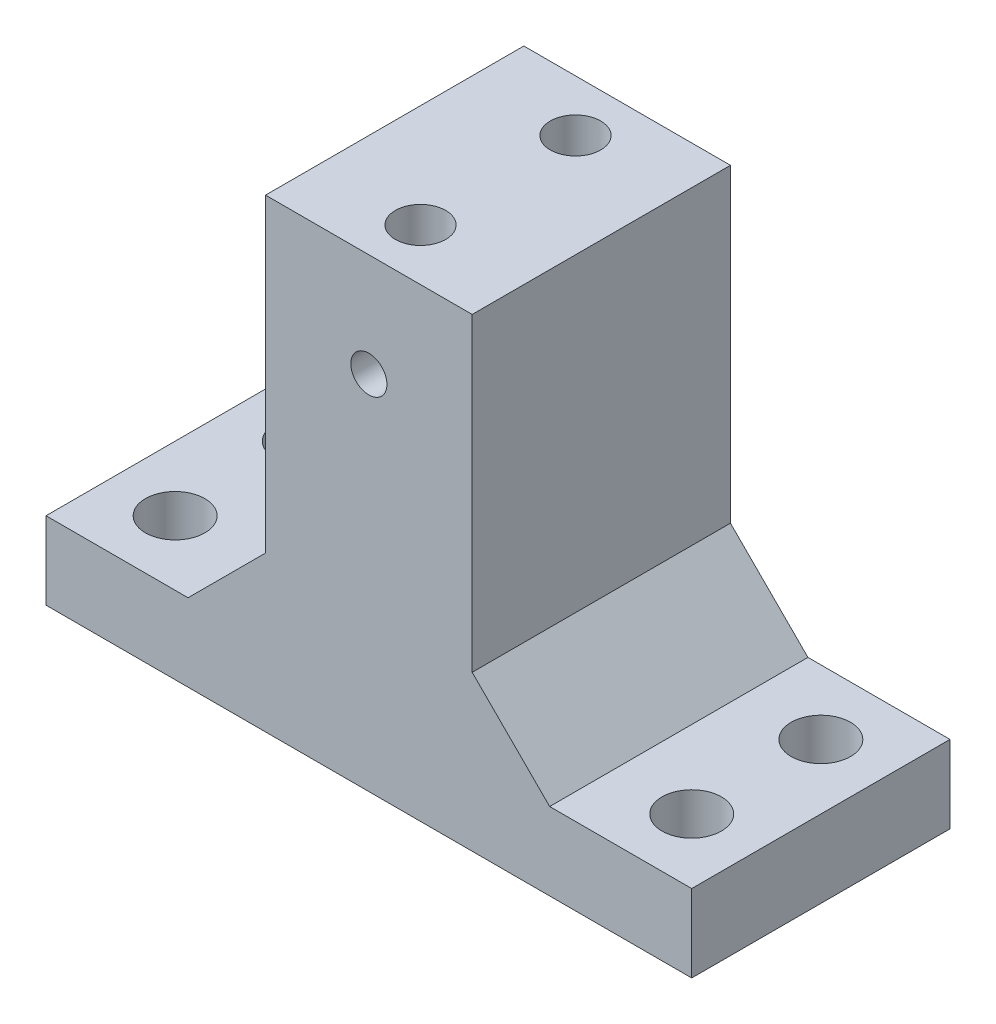
SolidWorks part; units mm, degrees
ref_plane "Front Plane" through (0, 0, 0) normal (0, 0, 1) x (1, 0, 0)
ref_plane "Top Plane" through (0, 0, 0) normal (0, 1, 0) x (1, 0, 0)
ref_plane "Right Plane" through (0, 0, 0) normal (1, 0, 0) x (0, 0, -1)
sketch "Sketch1" plane through (0, 0, 0) normal (0, 1, 0) x (1, 0, 0)
  line L1 (-12.5, -5) -> (12.5, -5)
  line L2 (-12.5, -5) -> (-12.5, 5)
  line L3 (-12.5, 5) -> (12.5, 5)
  line L4 (12.5, -5) -> (12.5, 5)
  line L5 (-12.5, -5) -> (12.5, 5) construction
  line L6 (-12.5, 5) -> (12.5, -5) construction
  line L7 (-10, -2.5) -> (10, -2.5) construction
  line L8 (-10, -2.5) -> (-10, 2.5) construction
  line L9 (-10, 2.5) -> (10, 2.5) construction
  line L10 (10, -2.5) -> (10, 2.5) construction
  line L11 (-10, -2.5) -> (10, 2.5) construction
  line L12 (-10, 2.5) -> (10, -2.5) construction
  circle A0 centre (-10, 2.5) radius 1.15
  circle A1 centre (-10, -2.5) radius 1.15
  circle A2 centre (10, 2.5) radius 1.15
  circle A3 centre (10, -2.5) radius 1.15
  point P0 (0, 0)
  point P6 (0, 0)
  dimension "D3" = 5
  dimension "D5" = 2.3
  dimension "D1" = 25
  dimension "D2" = 10
  dimension "D4" = 20
extrude "Boss-Extrude1" add sketch "Sketch1" along normal blind 3
sketch "Sketch3" plane through (0, 0, -5) normal (0, 0, -1) x (-1, 0, 0)
  line L0 (-12.5, 0) -> (12.5, 0) construction
  line L1 (-4, 0) -> (4, 0)
  line L2 (-4, 0) -> (-4, 18)
  line L3 (-4, 18) -> (4, 18)
  line L4 (4, 0) -> (4, 18)
  line L5 (0, 0) -> (0, 14) construction
  line L6 (0, 14) -> (0, 18) construction
  circle A0 centre (0, 14) radius 0.7
  dimension "D4" = 1.4
  dimension "D1" = 14
  dimension "D2" = 8
  dimension "D3" = 4
extrude "Boss-Extrude2" add sketch "Sketch3" against normal up to surface (10 mm away) up to face at (0, 1.5, 5)
sketch "Sketch5" plane through (0, 18, 0) normal (0, 1, 0) x (1, 0, 0)
  line L0 (0, 3) -> (0, -3) construction
  line L1 (-4, 5) -> (4, 5) construction
  circle A0 centre (0, 3) radius 0.975
  circle A2 centre (0, -3) radius 0.975
  dimension "D1" = 1.95
  dimension "D2" = 2
extrude "Cut-Extrude2" cut sketch "Sketch5" against normal blind 3.5
chamfer "Chamfer1" distance 3 angle 45 2 edges at (-4, 3, 0) (4, 3, 0)
